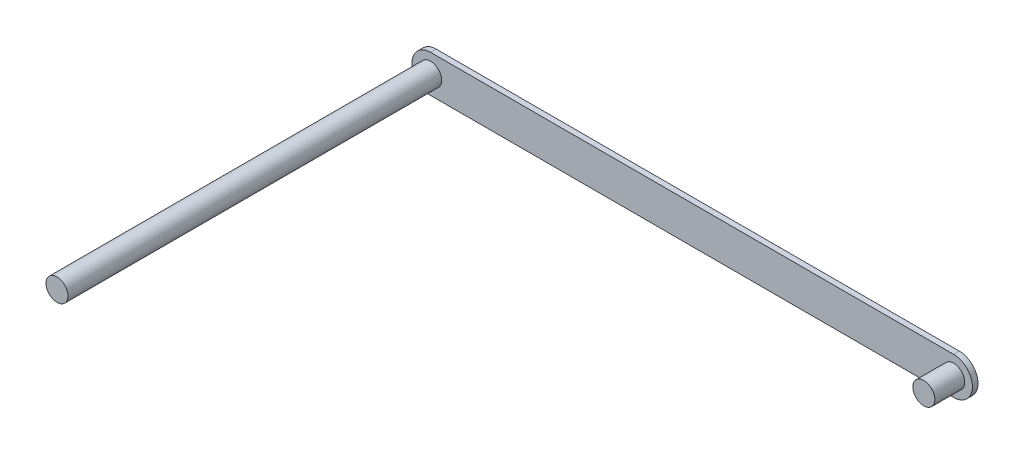
SolidWorks part; units mm, degrees
material "PBT General Purpose"
ref_plane "Front Plane" through (0, 0, 0) normal (0, 0, 1) x (1, 0, 0)
ref_plane "Top Plane" through (0, 0, 0) normal (0, 1, 0) x (1, 0, 0)
ref_plane "Right Plane" through (0, 0, 0) normal (1, 0, 0) x (0, 0, -1)
sketch "Sketch1" plane through (0, 0, 0) normal (0, 0, 1) x (1, 0, 0)
  line L0 (0, 5) -> (140, 5)
  line L6 (0, -5) -> (140, -5)
  arc A2 (0, 5) -> (0, -5) centre (0, 0) ccw
  arc A3 (140, -5) -> (140, 5) centre (140, 0) ccw
  dimension "D1" = 10
  dimension "D2" = 140
extrude "Boss-Extrude1" add sketch "Sketch1" along normal blind 1.5
sketch "Sketch2" plane through (0, 0, 1.5) normal (0, 0, 1) x (1, 0, 0)
  circle A0 centre (0, 0) radius 2.95
  circle A1 centre (140, 0) radius 2.95
  dimension "D1" = 5.9
  dimension "D2" = 140
extrude "Boss-Extrude2" add sketch "Sketch2" along normal blind 8
sketch "Sketch3" plane through (0, 0, 9.5) normal (0, 0, 1) x (1, 0, 0)
  circle A0 centre (0, 0) radius 2.95 construction
  circle A1 centre (0, 0) radius 2.95
extrude "Boss-Extrude3" add sketch "Sketch3" along normal blind 92
